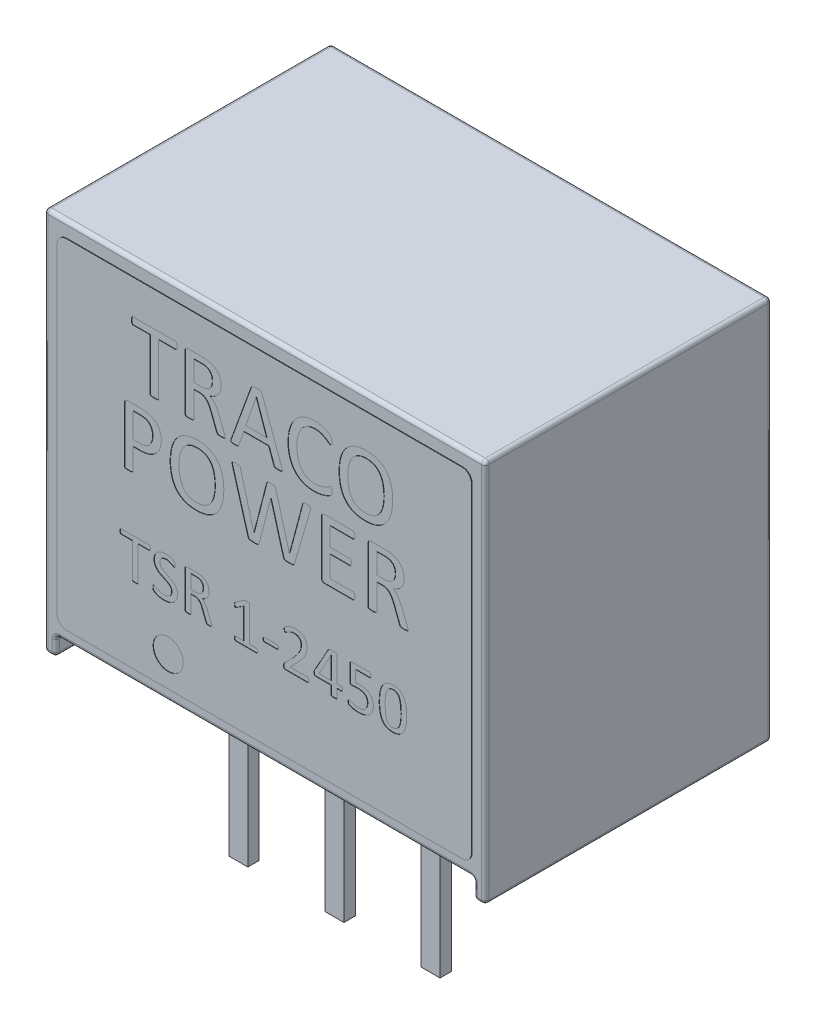
SolidWorks part; units mm, degrees
ref_plane "Front Plane" through (0, 0, 0) normal (0, 0, 1) x (1, 0, 0)
ref_plane "Top Plane" through (0, 0, 0) normal (0, 1, 0) x (1, 0, 0)
ref_plane "Right Plane" through (0, 0, 0) normal (1, 0, 0) x (0, 0, -1)
sketch "Sketch1" plane through (0, 0, 0) normal (0, 0, 1) x (1, 0, 0)
  line L0 (0, 0) -> (0, 25.4281) construction
  line L1 (5.55, 0.5) -> (-5.55, 0.5)
  line L2 (-5.55, 0.5) -> (-5.55, 0)
  line L3 (-5.55, 0) -> (-5.85, 0)
  line L4 (-5.85, 0) -> (-5.85, 10.2)
  line L5 (-5.85, 10.2) -> (5.85, 10.2)
  line L6 (5.85, 0) -> (5.85, 10.2)
  line L7 (5.55, 0) -> (5.85, 0)
  line L8 (5.55, 0.5) -> (5.55, 0)
  point P13 (0, 0.5)
  dimension "D1" = 0.3
  dimension "D2" = 0.5
  dimension "D3" = 11.1
  dimension "D4" = 10.2
extrude "Unit Body" add sketch "Sketch1" along normal mid plane 7.6
sketch "Sketch2" plane through (0, 0.5, 0) normal (0, -1, 0) x (1, 0, 0)
  line L0 (-2.55, 1.95) -> (-2.55, 1.65) construction
  line L1 (-2.8, 1.95) -> (-2.3, 1.95)
  line L2 (-2.8, 1.95) -> (-2.8, 1.65)
  line L3 (-2.8, 1.65) -> (-2.3, 1.65)
  line L4 (-2.3, 1.95) -> (-2.3, 1.65)
  line L5 (-5.85, 3.8) -> (-5.85, -3.8) construction
  line L6 (-2.3, 1.8) -> (-2.8, 1.8) construction
  line L7 (-5.55, 3.8) -> (5.55, 3.8) construction
  line L8 (0, 3.8) -> (0, -3.8) construction
  line L9 (-5.55, -3.8) -> (5.55, -3.8) construction
  line L10 (2.3, 1.8) -> (2.8, 1.8) construction
  line L11 (-0.25, 1.65) -> (0.25, 1.65)
  line L12 (-0.25, 1.65) -> (-0.25, 1.95)
  line L13 (-0.25, 1.95) -> (0.25, 1.95)
  line L14 (0.25, 1.65) -> (0.25, 1.95)
  line L15 (-0.25, 1.65) -> (0.25, 1.95) construction
  line L16 (-0.25, 1.95) -> (0.25, 1.65) construction
  line L17 (2.55, 1.95) -> (2.55, 1.65) construction
  line L18 (2.3, 1.95) -> (2.3, 1.65)
  line L19 (2.8, 1.65) -> (2.3, 1.65)
  line L20 (2.8, 1.95) -> (2.8, 1.65)
  line L21 (2.8, 1.95) -> (2.3, 1.95)
  point P17 (0, 1.8)
  dimension "D1" = 0.3
  dimension "D2" = 0.5
  dimension "D3" = 3.3
  dimension "D4" = 2
  dimension "D5" = 0.5
extrude "Pins" add sketch "Sketch2" along normal blind 4.6 separate body
fillet "Fillet1" radius 0.1 23 edges at (5.7, 0, 3.8) (5.55, 0.25, 3.8) (5.55, 0.5, 0) (5.55, 0, 0) (5.7, 0, -3.8) (5.55, 0.25, -3.8) (0, 0.5, -3.8) (-5.55, 0.25, -3.8) (-5.85, 5.1, -3.8) (-5.85, 0, 0) (-5.55, 0.5, 0) (-5.55, 0, 0) (0, 0.5, 3.8) (-5.55, 0.25, 3.8) (-5.7, 0, 3.8) (-5.85, 5.1, 3.8) (-5.85, 10.2, 0) (0, 10.2, 3.8) (0, 10.2, -3.8) (5.85, 5.1, -3.8) (5.85, 10.2, 0) (5.85, 5.1, 3.8) (5.85, 0, 0)
sketch "Sketch3" plane through (0, 0, 3.8) normal (0, 0, 1) x (1, 0, 0)
  line L0 (5.75, 10.1) -> (-5.75, 10.1) construction
  line L3 (0, 10.1) -> (0, 1.4972) construction
  line L4 (-5.25, 0.8) -> (5.25, 0.8)
  line L5 (-5.5, 1.05) -> (-5.5, 9.55)
  line L6 (-5.25, 9.8) -> (5.25, 9.8)
  line L7 (5.5, 1.05) -> (5.5, 9.55)
  line L8 (-5.5, 0.8) -> (5.5, 9.8) construction
  line L9 (-5.5, 9.8) -> (5.5, 0.8) construction
  arc A0 (-5.25, 0.8) -> (-5.5, 1.05) centre (-5.25, 1.05) cw
  arc A1 (5.25, 0.8) -> (5.5, 1.05) centre (5.25, 1.05) ccw
  arc A2 (5.25, 9.8) -> (5.5, 9.55) centre (5.25, 9.55) cw
  arc A3 (-5.5, 9.55) -> (-5.25, 9.8) centre (-5.25, 9.55) cw
  point P6 (0, 5.3)
  dimension "D4" = 0.25
  dimension "D1" = 9
  dimension "D2" = 0.3
  dimension "D3" = 11
extrude "Label" add sketch "Sketch3" along normal blind 0.015
sketch "Sketch4" plane through (0, 0, 3.815) normal (0, 0, 1) x (1, 0, 0)
  line L0 (-5.5, 7.3) -> (5.5, 7.3) construction
  line L1 (-5.5, 9.55) -> (-5.5, 1.05) construction
  line L2 (5.5, 1.05) -> (5.5, 9.55) construction
  line L3 (-5.5, 5.3) -> (5.5, 5.3) construction
  line L4 (-5.5, 9.55) -> (-5.5, 1.05) construction
  line L5 (5.25, 9.8) -> (-5.25, 9.8) construction
  line L6 (-2.55, 0.5) -> (-2.55, 1.6) construction
  line L7 (-5.5, 2.8) -> (5.5, 2.8) construction
  line L8 (-2.3, 0.5) -> (-2.8, 0.5) construction
  circle A0 centre (-2.55, 1.6) radius 0.4
  text T0 "TRACO" font "Calibri" height in points 6
  text T1 "POWER" font "Calibri" height in points 6
  text T3 "TSR 1-2450" font "Calibri" height in points 4
  dimension "D5" = 1.1
  dimension "D3" = 0.8
  dimension "D1" = 2.5
  dimension "D2" = 2
  dimension "D4" = 2.5
extrude "Label ID" cut sketch "Sketch4" against normal blind 0.01
sketch "Pin Locating Sketch" plane through (0, -4.1, 0) normal (0, -1, 0) x (1, 0, 0)
  line L0 (-2.8, 1.8) -> (-2.3, 1.8) construction
  line L1 (-2.8, 1.95) -> (-2.8, 1.65) construction
  line L2 (-2.3, 1.65) -> (-2.3, 1.95) construction
  line L3 (0.25, 1.8) -> (-0.25, 1.8) construction
  line L4 (0.25, 1.65) -> (0.25, 1.95) construction
  line L5 (-0.25, 1.95) -> (-0.25, 1.65) construction
  line L6 (2.3, 1.8) -> (2.8, 1.8) construction
  line L7 (2.3, 1.95) -> (2.3, 1.65) construction
  line L8 (2.8, 1.65) -> (2.8, 1.95) construction
  circle A0 centre (-2.55, 1.8) radius 0.15 construction
  circle A1 centre (0, 1.8) radius 0.15 construction
  circle A2 centre (2.55, 1.8) radius 0.15 construction
